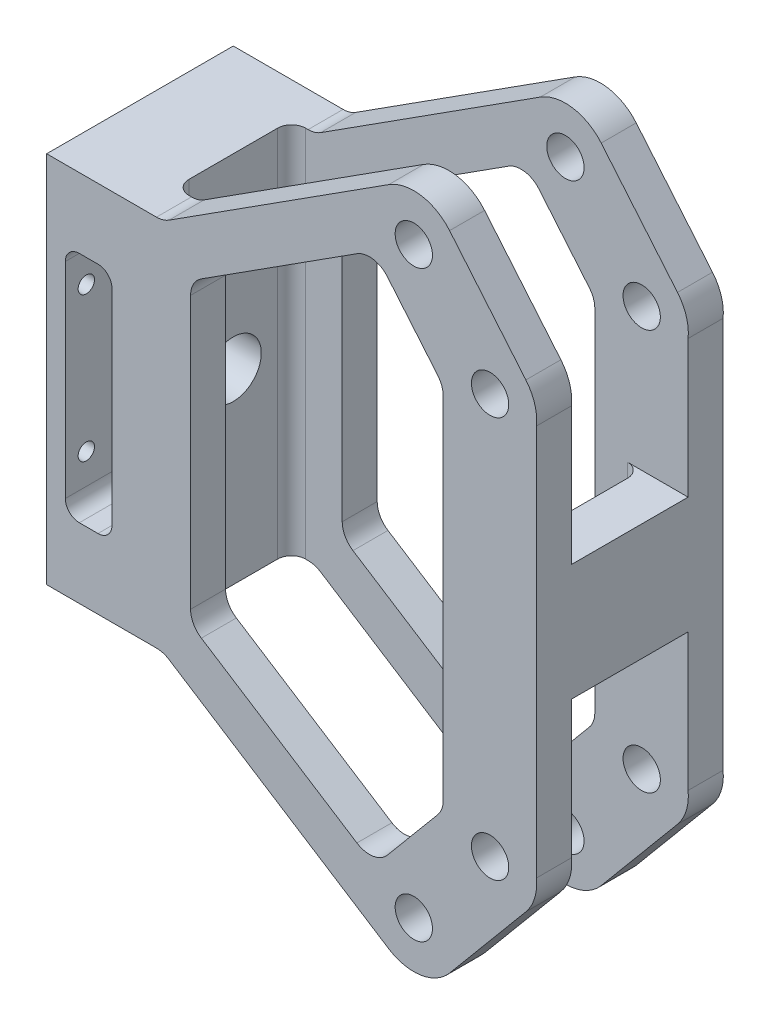
SolidWorks part; units mm, degrees
ref_plane "Front Plane" through (0, 0, 0) normal (0, 0, 1) x (1, 0, 0)
ref_plane "Top Plane" through (0, 0, 0) normal (0, 1, 0) x (1, 0, 0)
ref_plane "Right Plane" through (0, 0, 0) normal (1, 0, 0) x (0, 0, -1)
sketch "Sketch1" plane through (0, 0, 0) normal (0, 0, 1) x (1, 0, 0)
  line L0 (25, 0) -> (73.3089, -30.9223)
  line L1 (0, 0) -> (25, 0)
  line L2 (0, 0) -> (0, 80)
  line L3 (0, 80) -> (25, 80)
  line L4 (105, 0) -> (105, 80)
  line L5 (86.3709, -28.9153) -> (102.7209, -9.3653)
  line L6 (0, 40) -> (105, 40) construction
  line L7 (105, 0) -> (105, -1.9513)
  line L8 (105, 80) -> (105, 81.9513)
  line L9 (86.3709, 108.9153) -> (102.7209, 89.3653)
  line L10 (25, 80) -> (73.3089, 110.9223)
  line L11 (30.8528, 71.8732) -> (30.8528, 8.1268)
  line L12 (70.2091, 97.065) -> (85, 79.3793)
  line L13 (70.2091, -17.065) -> (85, 0.6207)
  line L14 (85, 0.6207) -> (85, 79.3793)
  line L15 (30.8528, 8.1268) -> (70.2091, -17.065)
  line L18 (30.8528, 71.8732) -> (70.2091, 97.065)
  line L28 (30.3911, 71.5777) -> (78.7, 102.5) construction
  circle A0 centre (78.7, -22.5) radius 4
  circle A1 centre (95.05, -2.95) radius 4
  arc A2 (73.3089, -30.9223) -> (86.3709, -28.9153) centre (78.7, -22.5) ccw
  arc A3 (102.7209, -9.3653) -> (105, -1.9513) centre (95.05, -2.95) ccw
  circle A4 centre (78.7, 102.5) radius 4
  circle A5 centre (95.05, 82.95) radius 4
  arc A6 (102.7209, 89.3653) -> (105, 81.9513) centre (95.05, 82.95) cw
  arc A7 (73.3089, 110.9223) -> (86.3709, 108.9153) centre (78.7, 102.5) cw
  point P28 (85, 40)
  point P32 (30.8528, 40)
  dimension "D5" = 8
  dimension "D8" = 8
  dimension "D9" = 20
  dimension "D10" = 20
  dimension "D1" = 80
  dimension "D2" = 105
  dimension "D3" = 22.5
  dimension "D4" = 78.7
  dimension "D6" = 2.95
  dimension "D7" = 95.05
  dimension "D11" = 25
  dimension "D12" = 80
  dimension "D16" = 20
  dimension "D13" = 20
  dimension "D15" = 30.8528
  dimension "D14" = 10
extrude "Boss-Extrude1" add sketch "Sketch1" against normal blind 40
sketch "Sketch2" plane through (0, 0, 0) normal (0, 1, 0) x (1, 0, 0)
  line L0 (0, 40) -> (0, 0) construction
  line L1 (20, 32.5) -> (120, 32.5)
  line L2 (20, 32.5) -> (20, 7.5)
  line L3 (20, 7.5) -> (120, 7.5)
  line L4 (120, 32.5) -> (120, 7.5)
  line L5 (102.7209, 0) -> (86.3709, 0) construction
  dimension "D1" = 20
  dimension "D2" = 25
  dimension "D3" = 7.5
  dimension "D4" = 100
extrude "Cut-Extrude1" cut sketch "Sketch2" against normal through all both and the other way through all
sketch "Sketch3" plane through (105, 0, 0) normal (1, 0, 0) x (0, 0, -1)
  line L0 (0, -1.9513) -> (0, 81.9513) construction
  line L1 (0, 40) -> (40, 40) construction
  line L2 (40, -1.9513) -> (40, 81.9513) construction
  line L4 (7.5, 27.5) -> (32.5, 27.5)
  line L5 (7.5, 27.5) -> (7.5, 52.5)
  line L6 (7.5, 52.5) -> (32.5, 52.5)
  line L7 (32.5, 27.5) -> (32.5, 52.5)
  line L8 (7.5, 27.5) -> (32.5, 52.5) construction
  line L9 (7.5, 52.5) -> (32.5, 27.5) construction
  point P6 (20, 40)
  dimension "D1" = 25
  dimension "D2" = 25
extrude "Boss-Extrude2" add sketch "Sketch3" against normal blind 10
sketch "Sketch4" plane through (0, 0, 0) normal (-1, 0, 0) x (0, 0, 1)
  line L2 (0, 80) -> (0, 0) construction
  line L3 (-40, 80) -> (0, 80) construction
  circle A0 centre (-20, 40) radius 6
  dimension "D1" = 12
  dimension "D2" = 20
  dimension "D3" = 40
extrude "Cut-Extrude2" cut sketch "Sketch4" against normal blind 100
fillet "Fillet1" radius 5 16 edges at (25, 0, -3.75) (25, 0, -36.25) (25, 80, -36.25) (25, 80, -3.75) (30.8528, 71.8732, -3.75) (30.8528, 8.1268, -36.25) (30.8528, 71.8732, -36.25) (70.2091, 97.065, -36.25) (85, 79.3793, -36.25) (70.2091, 97.065, -3.75) (85, 79.3793, -3.75) (70.2091, -17.065, -36.25) (85, 0.6207, -36.25) (85, 0.6207, -3.75) (70.2091, -17.065, -3.75) (30.8528, 8.1268, -3.75)
fillet "Fillet2" radius 3 4 edges at (20, 40, -32.5) (20, 40, -7.5) (95, 40, -32.5) (95, 40, -7.5)
sketch "Sketch5" plane through (0, 0, 0) normal (-1, 0, 0) x (0, 0, 1)
  line L1 (-35.5, 24.5) -> (-4.5, 24.5) construction
  line L2 (-35.5, 24.5) -> (-35.5, 55.5) construction
  line L3 (-35.5, 55.5) -> (-4.5, 55.5) construction
  line L4 (-4.5, 24.5) -> (-4.5, 55.5) construction
  line L5 (-35.5, 24.5) -> (-4.5, 55.5) construction
  line L6 (-35.5, 55.5) -> (-4.5, 24.5) construction
  circle A0 centre (-35.5, 55.5) radius 1.75
  circle A1 centre (-4.5, 55.5) radius 1.75
  circle A2 centre (-35.5, 24.5) radius 1.75
  circle A3 centre (-4.5, 24.5) radius 1.75
  point P0 (-20, 40)
  dimension "D3" = 3.5
  dimension "D4" = 3.5
  dimension "D5" = 3.5
  dimension "D6" = 3.5
  dimension "D1" = 31
  dimension "D2" = 31
extrude "Cut-Extrude3" cut sketch "Sketch5" against normal blind 10
sketch "Sketch7" plane through (0, 0, 0) normal (0, 0, 1) x (1, 0, 0)
  line L0 (0, 40) -> (30.8528, 40) construction
  line L1 (0, 80) -> (0, 0) construction
  line L3 (4, 65) -> (4, 15)
  line L4 (4, 15) -> (14, 15)
  line L5 (14, 15) -> (14, 65)
  line L6 (14, 65) -> (4, 65)
  dimension "D1" = 25
  dimension "D2" = 25
  dimension "D3" = 4
  dimension "D4" = 10
extrude "Cut-Extrude4" cut sketch "Sketch7" against normal blind 10
fillet "Fillet3" radius 3 4 edges at (14, 15, -5) (4, 15, -5) (14, 65, -5) (4, 65, -5)
ref_plane "Plane1" through (0, 0, -20) normal (0, 0, 1) x (1, 0, 0)
mirror "Mirror1" about plane through (0, 0, -20) normal (0, 0, 1) of "Fillet3", "Cut-Extrude4"
